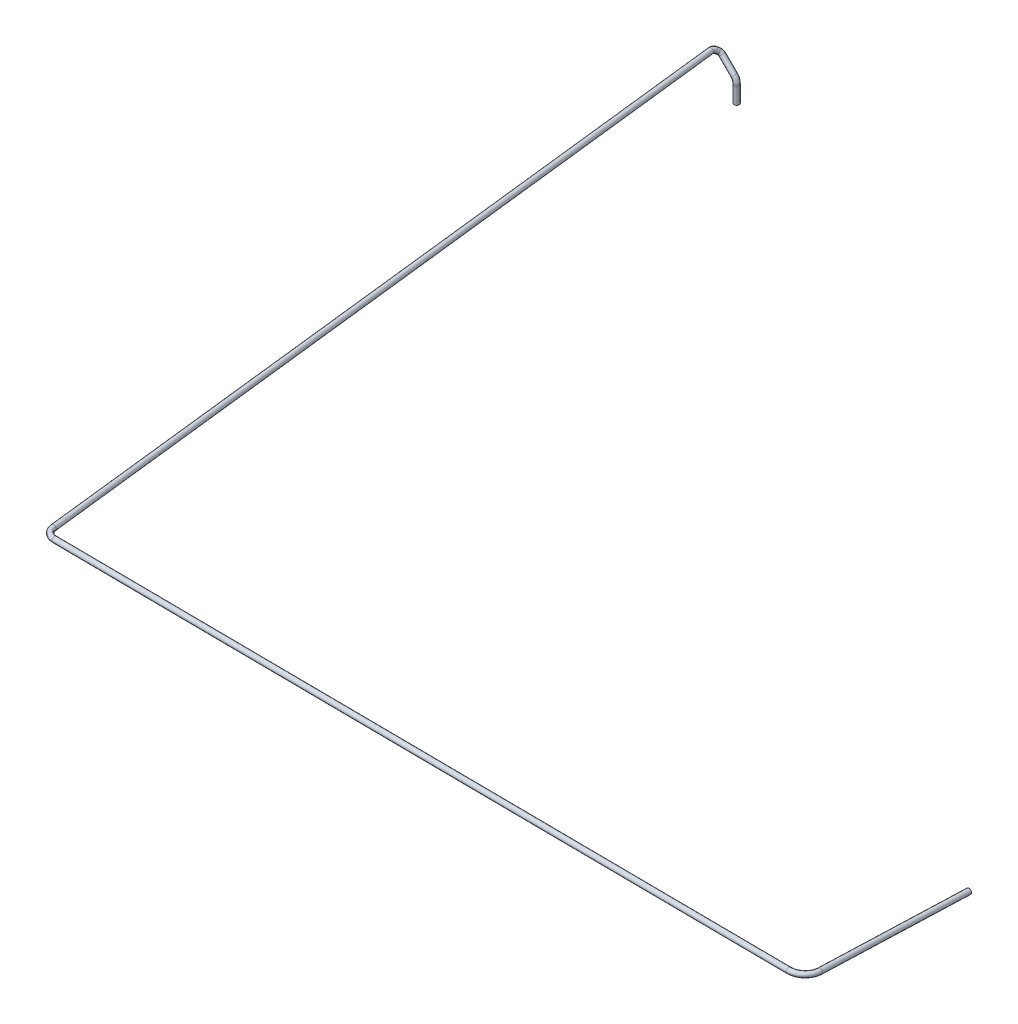
SolidWorks part; units mm, degrees
ref_plane "Front Plane" through (0, 0, 0) normal (0, 0, 1) x (1, 0, 0)
ref_plane "Top Plane" through (0, 0, 0) normal (0, 1, 0) x (1, 0, 0)
ref_plane "Right Plane" through (0, 0, 0) normal (1, 0, 0) x (0, 0, -1)
sketch3d "3DSketch2"
  line L0 (6.5, 1.5607, 70) -> (6.5, 2.5607, 70) construction
  line L1 (-1.6361, 3.9093, 0.75) -> (-1.9093, 3.6361, 0.75) construction
  line L2 (-1.7727, 3.7727, 0.75) -> (-1.6875, 3.6875, 0.625) construction
  line L3 (-1.6875, 3.6875, 0.625) -> (-1.8147, 3.8147, 0.4514) construction
  line L4 (-1.9915, 3.6379, 0.4514) -> (-1.6379, 3.9915, 0.4514) construction
  line L5 (0, 0, 0) -> (0, 1.5441, 0)
  line L6 (0, 1.5441, 0) -> (0, 1.6893, 0)
  line L7 (-0.2197, 2.2197, 0) -> (-1.3566, 3.3566, 0)
  line L8 (-1.6111, 3.6111, 0.1529) -> (-1.7036, 3.7036, 0.2885)
  line L9 (-1.7927, 3.8107, 0.6768) -> (5.0383, 2.5547, 70.4645)
  line L10 (6.0318, 2.5325, 71.3668) -> (76.482, 2.0623, 71.4831)
  line L11 (7.114, 2.5607, 71.3686) -> (7.114, 2.5253, 71.3686) construction
  line L12 (77.9841, 2.0055, 69.991) -> (78.0486, 1.5607, 55.7934)
  line L13 (77.983, 2.0128, 70.225) -> (77.983, 2.0607, 70.225) construction
  line L14 (76.5, 1.5607, 70) -> (76.5, 2.0607, 70) construction
  circle A0 centre (6.5, 4.5607, 70) radius 2 construction
  circle A1 centre (6.5, 1.5607, 70) radius 1 construction
  circle A2 centre (6.5, 1.5607, 70) radius 1 construction
  circle A3 centre (6.5, 2.5607, 70) radius 1.5 construction
  circle A4 centre (-1.8147, 3.8147, 0.4514) radius 0.25 construction
  arc A6 (0, 1.6893, 0) -> (-0.2197, 2.2197, 0) centre (-0.75, 1.6893, 0) ccw
  arc A7 (-1.7036, 3.7036, 0.2885) -> (-1.7927, 3.8107, 0.6768) centre (-1.4233, 3.4762, 0.6346) ccw
  arc A8 (-1.3566, 3.3566, 0) -> (-1.6111, 3.6111, 0.1529) centre (-1.3566, 3.3566, 0.5) ccw
  arc A9 (5.0383, 2.5547, 70.4645) -> (6.0318, 2.5325, 71.3668) centre (6.0336, 2.5498, 70.367) ccw
  circle A10 centre (76.5, 1.5607, 70) radius 0.889 construction
  circle A11 centre (76.5, 1.5607, 70) radius 0.889 construction
  circle A12 centre (76.5, 2.0607, 70) radius 1.5 construction
  arc A13 (76.482, 2.0623, 71.4831) -> (77.9841, 2.0055, 69.991) centre (76.4841, 2.0153, 69.9838) ccw
  spline S0 degree 3 poles (-1.9093, 3.6361, 0.75) (-1.8718, 3.6455, 0.7292) (-1.8344, 3.6522, 0.7072) (-1.7788, 3.6606, 0.673) (-1.7604, 3.663, 0.6613) (-1.7326, 3.668, 0.6444) (-1.7232, 3.6698, 0.6388) (-1.7045, 3.6758, 0.6291) (-1.6945, 3.6801, 0.6248) (-1.6792, 3.6961, 0.6252) (-1.6752, 3.706, 0.6298) (-1.6695, 3.7247, 0.6396) (-1.6677, 3.7339, 0.6452) (-1.6629, 3.7615, 0.662) (-1.6604, 3.7798, 0.6736) (-1.6521, 3.835, 0.7075) (-1.6454, 3.872, 0.7294) (-1.6361, 3.9093, 0.75) knots 0 0 0 0 0.25 0.25 0.375 0.375 0.4375 0.4375 0.5 0.5 0.5625 0.5625 0.625 0.625 0.75 0.75 1 1 1 1 construction
  point P3 (6.5, 4.0607, 70)
  point P5 (6.5, 0.5607, 70)
  point P7 (6.5, 0.5607, 70)
  point P8 (-1.6875, 3.6875, 0.625)
  point P20 (-1.8147, 3.8147, 0.4514)
  point P26 (-1.6875, 3.6875, 0.625)
  point P28 (-1.692, 3.692, 0.2715)
  point P35 (0, 2, 0)
  point P36 (-0.75, 1.6893, 0.75)
  point P39 (6.5, 2.5607, 70)
  point P42 (-1.8147, 3.8147, 0.4514)
  point P44 (-1.0898, 3.8478, 0.6086)
  point P47 (-1.5068, 3.5068, 0)
  point P48 (-1.0031, 3.7102, 0.5)
  point P49 (5.0061, 2.5607, 70.1356)
  point P55 (5.1265, 2.5385, 71.3653)
  point P56 (6.0402, 3.5496, 70.3843)
  point P59 (76.5, 2.4497, 70)
  point P61 (76.5, 2.4497, 70)
  point P63 (76.7219, 2.0607, 71.4835)
  point P67 (76.5, 3.5607, 70)
  point P71 (77.9773, 2.0523, 71.4856)
  point P72 (76.4942, 3.5146, 69.9369)
  dimension "D1" = 3
  dimension "D2" = 0.5
  dimension "D3" = 0.75
  dimension "D4" = 1
  dimension "D5" = 0.5
  dimension "D6" = 1
  dimension "D7" = 3
  dimension "D8" = 0.5
  dimension "D9" = 1.5
  dimension "D10" = 15.7
sketch "Sketch4" plane through (0, 0, 0) normal (0, 1, 0) x (-1, 0, 0)
  circle A2 centre (0, 0) radius 0.25
  dimension "D1" = 0.5
ref_plane "Plane1" through (-2.2652, 3.7348, 0.75) normal (0.7071, -0.7071, 0) x (0, 0, -1)
ref_plane "Plane2" through (0, 0, 0.75) normal (0, 0, 1) x (1, 0, 0)
sweep "Sweep3" add profiles "Sketch4" path "3DSketch2"
